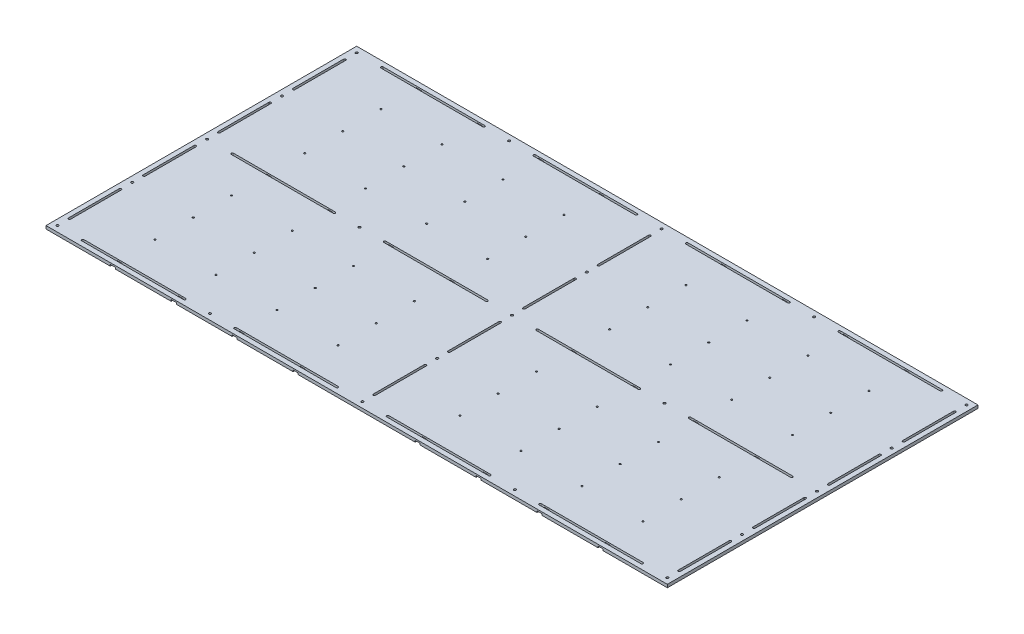
SolidWorks part; units mm, degrees
material "Pine"
ref_plane "Front" through (0, 0, 0) normal (0, 0, 1) x (1, 0, 0)
ref_plane "Top" through (0, 0, 0) normal (0, 1, 0) x (1, 0, 0)
ref_plane "Right" through (0, 0, 0) normal (1, 0, 0) x (0, 0, -1)
sketch "Sketch1" plane through (0, 0, 0) normal (0, 1, 0) x (1, 0, 0)
  line L0 (-1220, 610) -> (1220, -610) construction
  line L1 (-1220, 610) -> (1220, 610)
  line L2 (-1220, 610) -> (-1220, -610)
  line L3 (-1220, -610) -> (1220, -610)
  line L4 (1220, 610) -> (1220, -610)
  dimension "D1" = 2440
  dimension "D2" = 1220
extrude "Boss-Extrude1" add sketch "Sketch1" along normal blind 12
sketch "Sketch3" plane through (0, 0, 0) normal (0, -1, 0) x (1, 0, 0)
  line L0 (-1220, 610) -> (1220, 610) construction
  line L1 (-968, 610) -> (-948, 610)
  line L2 (-968, 610) -> (-968, -610)
  line L3 (-968, -610) -> (-948, -610)
  line L4 (-948, 610) -> (-948, -610)
  line L5 (1220, -610) -> (-1220, -610) construction
  line L7 (-1220, 610) -> (-1175, 610) construction
  line L8 (-1220, 610) -> (-1220, -610) construction
  line L9 (-1220, -610) -> (-1175, -610) construction
  line L10 (-1175, 610) -> (-1175, -610) construction
  line L11 (-22.5, 610) -> (22.5, 610) construction
  line L12 (-22.5, 610) -> (-22.5, -610) construction
  line L13 (-22.5, -610) -> (22.5, -610) construction
  line L14 (22.5, 610) -> (22.5, -610) construction
  line L15 (1220, 610) -> (1175, 610) construction
  line L16 (1220, 610) -> (1220, -610) construction
  line L17 (1220, -610) -> (1175, -610) construction
  line L18 (1175, 610) -> (1175, -610) construction
  line L19 (-1220, 610) -> (1220, 610) construction
  line L20 (-1220, 610) -> (-1220, 565) construction
  line L21 (-1220, 565) -> (1220, 565) construction
  line L22 (1220, 610) -> (1220, 565) construction
  line L23 (1220, 22.5) -> (-1220, 22.5) construction
  line L24 (1220, 22.5) -> (1220, -22.5) construction
  line L25 (1220, -22.5) -> (-1220, -22.5) construction
  line L26 (-1220, 22.5) -> (-1220, -22.5) construction
  line L27 (-1220, -610) -> (1220, -610) construction
  line L28 (-1220, -610) -> (-1220, -565) construction
  line L29 (-1220, -565) -> (1220, -565) construction
  line L30 (1220, -610) -> (1220, -565) construction
  line L31 (-1197.5, 610) -> (-1197.5, -610) construction
  line L32 (0, -610) -> (0, 610) construction
  line L33 (1197.5, -610) -> (1197.5, 610) construction
  line L34 (-958, 610) -> (-958, -610) construction
  line L35 (-728.5, 610) -> (-708.5, 610)
  line L36 (-728.5, 610) -> (-728.5, -610)
  line L37 (-728.5, -610) -> (-708.5, -610)
  line L38 (-708.5, 610) -> (-708.5, -610)
  line L39 (-718.5, 610) -> (-718.5, -610) construction
  line L40 (-489, 610) -> (-469, 610)
  line L41 (-489, 610) -> (-489, -610)
  line L42 (-489, -610) -> (-469, -610)
  line L43 (-469, 610) -> (-469, -610)
  line L44 (-479, 610) -> (-479, -610) construction
  line L45 (-249.5, 610) -> (-229.5, 610)
  line L46 (-249.5, 610) -> (-249.5, -610)
  line L47 (-249.5, -610) -> (-229.5, -610)
  line L48 (-229.5, 610) -> (-229.5, -610)
  line L49 (-239.5, 610) -> (-239.5, -610) construction
  line L50 (239.5, 610) -> (239.5, -610) construction
  line L51 (479, 610) -> (479, -610) construction
  line L52 (718.5, 610) -> (718.5, -610) construction
  line L53 (958, 610) -> (958, -610) construction
  line L54 (229.5, 610) -> (229.5, -610)
  line L55 (249.5, -610) -> (229.5, -610)
  line L56 (249.5, 610) -> (249.5, -610)
  line L57 (249.5, 610) -> (229.5, 610)
  line L58 (469, 610) -> (469, -610)
  line L59 (489, -610) -> (469, -610)
  line L60 (489, 610) -> (489, -610)
  line L61 (489, 610) -> (469, 610)
  line L62 (708.5, 610) -> (708.5, -610)
  line L63 (728.5, -610) -> (708.5, -610)
  line L64 (728.5, 610) -> (728.5, -610)
  line L65 (728.5, 610) -> (708.5, 610)
  line L66 (948, 610) -> (948, -610)
  line L67 (968, -610) -> (948, -610)
  line L68 (968, 610) -> (968, -610)
  line L69 (968, 610) -> (948, 610)
  dimension "D1" = 20
  dimension "D2" = 45
  dimension "D3" = 22.5
  dimension "D4" = 45
  dimension "D5" = 22.5
  dimension "D6" = 239.5
  dimension "D8" = 239.5
  dimension "D7" = 4
extrude "Cut-Extrude1" cut sketch "Sketch3" against normal blind 6
hole_wizard "M8 Clearance Hole1" positions "Sketch7" profile "Sketch5" hole size "M8" standard "ISO" end condition through all
sketch "Sketch7" plane through (0, 12, 0) normal (0, 1, 0) x (1, 0, 0)
  line L0 (-1197.5, -610) -> (-1197.5, 610) construction
  line L1 (0, 610) -> (0, -610) construction
  line L2 (1197.5, 610) -> (1197.5, -610) construction
  line L3 (-1197.5, 587.5) -> (-1197.5, 0) construction
  line L4 (-1197.5, 0) -> (-1197.5, -587.5) construction
  line L6 (-1220, 610) -> (-1175, 610) construction
  line L7 (-1220, -610) -> (-1175, -610) construction
  line L25 (-718.5, 0) -> (-479, 0) construction
  line L26 (-718.5, -610) -> (-718.5, 610) construction
  line L27 (-479, -610) -> (-479, 610) construction
  line L29 (479, 0) -> (718.5, 0) construction
  line L30 (479, -610) -> (479, 610) construction
  line L31 (718.5, -610) -> (718.5, 610) construction
  point P0 (-1197.5, 587.5)
  point P4 (-1197.5, 293.75)
  point P6 (-1197.5, 0)
  point P8 (-1197.5, -293.75)
  point P10 (-1197.5, -587.5)
  point P12 (0, -587.5)
  point P16 (0, 0)
  point P19 (0, 587.5)
  point P21 (1197.5, 587.5)
  point P25 (1197.5, 293.75)
  point P27 (1197.5, 0)
  point P29 (1197.5, -293.75)
  point P31 (1197.5, -587.5)
  point P33 (0, -293.75)
  point P35 (0, 293.75)
  point P109 (598.75, 0)
  point P111 (-598.75, 0)
  point P114 (-598.75, -587.5)
  point P116 (-598.75, 587.5)
  point P120 (598.75, 587.5)
  point P122 (598.75, -587.5)
  dimension "D1" = 22.5
  dimension "D2" = 22.5
sketch "Sketch5" plane through (-1197.5, 12, -587.5) normal (1, 0, 0) x (0, 0, 1)
  line L0 (0, 0) -> (0, 12)
  line L1 (0, 12) -> (4.5, 12)
  line L2 (4.5, 12) -> (4.5, 0)
  line L5 (4.5, 0) -> (0, 0)
  line L11 (0, -6.35) -> (0, 107.95) construction
  dimension "Thru Hole Dia." = 9
  dimension "Thru Hole Depth" = 12
sketch "Sketch8" plane through (0, 12, 0) normal (0, 1, 0) x (1, 0, 0)
  line L0 (-1197.5, 587.5) -> (-598.75, 587.5) construction
  line L1 (-598.75, 587.5) -> (0, 587.5) construction
  line L2 (-1197.5, 587.5) -> (-1197.5, 293.75) construction
  line L3 (-1197.5, 293.75) -> (-1197.5, 0) construction
  line L4 (-1197.5, -610) -> (-1197.5, 610) construction
  line L5 (-1197.5, 0) -> (-598.75, 0) construction
  line L6 (-598.75, 0) -> (0, 0) construction
  line L7 (-1197.5, 0) -> (-1197.5, -293.75) construction
  line L8 (-1197.5, -293.75) -> (-1197.5, -587.5) construction
  line L9 (-1197.5, -587.5) -> (-598.75, -587.5) construction
  line L10 (-598.75, -587.5) -> (0, -587.5) construction
  line L11 (-1098.125, 587.5) -> (-698.125, 587.5) construction
  line L12 (-1098.125, 591.75) -> (-698.125, 591.75)
  line L13 (-1098.125, 583.25) -> (-698.125, 583.25)
  line L14 (-99.375, 587.5) -> (-499.375, 587.5) construction
  line L15 (-99.375, 583.25) -> (-499.375, 583.25)
  line L16 (-99.375, 591.75) -> (-499.375, 591.75)
  line L17 (-1197.5, 340.625) -> (-1197.5, 540.625) construction
  line L18 (-1201.75, 340.625) -> (-1201.75, 540.625)
  line L19 (-1193.25, 340.625) -> (-1193.25, 540.625)
  line L20 (-1197.5, 46.875) -> (-1197.5, 246.875) construction
  line L21 (-1201.75, 46.875) -> (-1201.75, 246.875)
  line L22 (-1193.25, 46.875) -> (-1193.25, 246.875)
  line L23 (-1197.5, -246.875) -> (-1197.5, -46.875) construction
  line L24 (-1201.75, -246.875) -> (-1201.75, -46.875)
  line L25 (-1193.25, -246.875) -> (-1193.25, -46.875)
  line L26 (-1197.5, -540.625) -> (-1197.5, -340.625) construction
  line L27 (-1201.75, -540.625) -> (-1201.75, -340.625)
  line L28 (-1193.25, -540.625) -> (-1193.25, -340.625)
  line L29 (-1098.125, -587.5) -> (-698.125, -587.5) construction
  line L30 (-1098.125, -583.25) -> (-698.125, -583.25)
  line L31 (-1098.125, -591.75) -> (-698.125, -591.75)
  line L32 (-99.375, -587.5) -> (-499.375, -587.5) construction
  line L33 (-99.375, -591.75) -> (-499.375, -591.75)
  line L34 (-99.375, -583.25) -> (-499.375, -583.25)
  line L35 (-99.375, 0) -> (-499.375, 0) construction
  line L36 (-99.375, -4.25) -> (-499.375, -4.25)
  line L37 (-99.375, 4.25) -> (-499.375, 4.25)
  line L38 (-1098.125, 0) -> (-698.125, 0) construction
  line L39 (-1098.125, 4.25) -> (-698.125, 4.25)
  line L40 (-1098.125, -4.25) -> (-698.125, -4.25)
  line L41 (0, -50) -> (0, 50) construction
  line L42 (1098.125, 587.5) -> (698.125, 587.5) construction
  line L43 (1098.125, 591.75) -> (698.125, 591.75)
  line L44 (1098.125, 583.25) -> (698.125, 583.25)
  line L45 (99.375, 587.5) -> (499.375, 587.5) construction
  line L46 (99.375, 583.25) -> (499.375, 583.25)
  line L47 (99.375, 591.75) -> (499.375, 591.75)
  line L48 (1197.5, 340.625) -> (1197.5, 540.625) construction
  line L49 (1201.75, 340.625) -> (1201.75, 540.625)
  line L50 (1193.25, 340.625) -> (1193.25, 540.625)
  line L51 (1197.5, 46.875) -> (1197.5, 246.875) construction
  line L52 (1201.75, 46.875) -> (1201.75, 246.875)
  line L53 (1193.25, 46.875) -> (1193.25, 246.875)
  line L54 (1197.5, -246.875) -> (1197.5, -46.875) construction
  line L55 (1201.75, -246.875) -> (1201.75, -46.875)
  line L56 (1193.25, -246.875) -> (1193.25, -46.875)
  line L57 (1197.5, -540.625) -> (1197.5, -340.625) construction
  line L58 (1201.75, -540.625) -> (1201.75, -340.625)
  line L59 (1193.25, -540.625) -> (1193.25, -340.625)
  line L60 (1098.125, -587.5) -> (698.125, -587.5) construction
  line L61 (1098.125, -583.25) -> (698.125, -583.25)
  line L62 (1098.125, -591.75) -> (698.125, -591.75)
  line L63 (99.375, -587.5) -> (499.375, -587.5) construction
  line L64 (99.375, -591.75) -> (499.375, -591.75)
  line L65 (99.375, -583.25) -> (499.375, -583.25)
  line L66 (99.375, 0) -> (499.375, 0) construction
  line L67 (99.375, -4.25) -> (499.375, -4.25)
  line L68 (99.375, 4.25) -> (499.375, 4.25)
  line L69 (1098.125, 0) -> (698.125, 0) construction
  line L70 (1098.125, 4.25) -> (698.125, 4.25)
  line L71 (1098.125, -4.25) -> (698.125, -4.25)
  line L72 (598.75, -587.5) -> (0, -587.5) construction
  line L73 (1197.5, -587.5) -> (598.75, -587.5) construction
  line L74 (1197.5, -293.75) -> (1197.5, -587.5) construction
  line L75 (1197.5, 0) -> (1197.5, -293.75) construction
  line L76 (598.75, 0) -> (0, 0) construction
  line L77 (1197.5, 0) -> (598.75, 0) construction
  line L78 (1197.5, 293.75) -> (1197.5, 0) construction
  line L79 (1197.5, 587.5) -> (1197.5, 293.75) construction
  line L80 (598.75, 587.5) -> (0, 587.5) construction
  line L81 (1197.5, 587.5) -> (598.75, 587.5) construction
  line L83 (0, 587.5) -> (0, 293.75) construction
  line L84 (0, 293.75) -> (0, 0) construction
  line L85 (0, 0) -> (0, -293.75) construction
  line L86 (0, -293.75) -> (0, -587.5) construction
  line L87 (0, 340.625) -> (0, 540.625) construction
  line L88 (-4.25, 340.625) -> (-4.25, 540.625)
  line L89 (4.25, 340.625) -> (4.25, 540.625)
  line L90 (0, 46.875) -> (0, 246.875) construction
  line L91 (-4.25, 46.875) -> (-4.25, 246.875)
  line L92 (4.25, 46.875) -> (4.25, 246.875)
  line L93 (0, -246.875) -> (0, -46.875) construction
  line L94 (-4.25, -246.875) -> (-4.25, -46.875)
  line L95 (4.25, -246.875) -> (4.25, -46.875)
  line L96 (0, -540.625) -> (0, -340.625) construction
  line L97 (-4.25, -540.625) -> (-4.25, -340.625)
  line L98 (4.25, -540.625) -> (4.25, -340.625)
  arc A0 (-1098.125, 591.75) -> (-1098.125, 583.25) centre (-1098.125, 587.5) ccw
  arc A1 (-698.125, 583.25) -> (-698.125, 591.75) centre (-698.125, 587.5) ccw
  arc A2 (-99.375, 583.25) -> (-99.375, 591.75) centre (-99.375, 587.5) ccw
  arc A3 (-499.375, 591.75) -> (-499.375, 583.25) centre (-499.375, 587.5) ccw
  arc A4 (-1201.75, 340.625) -> (-1193.25, 340.625) centre (-1197.5, 340.625) ccw
  arc A5 (-1193.25, 540.625) -> (-1201.75, 540.625) centre (-1197.5, 540.625) ccw
  arc A6 (-1201.75, 46.875) -> (-1193.25, 46.875) centre (-1197.5, 46.875) ccw
  arc A7 (-1193.25, 246.875) -> (-1201.75, 246.875) centre (-1197.5, 246.875) ccw
  arc A8 (-1201.75, -246.875) -> (-1193.25, -246.875) centre (-1197.5, -246.875) ccw
  arc A9 (-1193.25, -46.875) -> (-1201.75, -46.875) centre (-1197.5, -46.875) ccw
  arc A10 (-1201.75, -540.625) -> (-1193.25, -540.625) centre (-1197.5, -540.625) ccw
  arc A11 (-1193.25, -340.625) -> (-1201.75, -340.625) centre (-1197.5, -340.625) ccw
  arc A12 (-1098.125, -583.25) -> (-1098.125, -591.75) centre (-1098.125, -587.5) ccw
  arc A13 (-698.125, -591.75) -> (-698.125, -583.25) centre (-698.125, -587.5) ccw
  arc A14 (-99.375, -591.75) -> (-99.375, -583.25) centre (-99.375, -587.5) ccw
  arc A15 (-499.375, -583.25) -> (-499.375, -591.75) centre (-499.375, -587.5) ccw
  arc A16 (-99.375, -4.25) -> (-99.375, 4.25) centre (-99.375, 0) ccw
  arc A17 (-499.375, 4.25) -> (-499.375, -4.25) centre (-499.375, 0) ccw
  arc A18 (-1098.125, 4.25) -> (-1098.125, -4.25) centre (-1098.125, 0) ccw
  arc A19 (-698.125, -4.25) -> (-698.125, 4.25) centre (-698.125, 0) ccw
  arc A20 (1098.125, 591.75) -> (1098.125, 583.25) centre (1098.125, 587.5) cw
  arc A21 (698.125, 583.25) -> (698.125, 591.75) centre (698.125, 587.5) cw
  arc A22 (99.375, 583.25) -> (99.375, 591.75) centre (99.375, 587.5) cw
  arc A23 (499.375, 591.75) -> (499.375, 583.25) centre (499.375, 587.5) cw
  arc A24 (1201.75, 340.625) -> (1193.25, 340.625) centre (1197.5, 340.625) cw
  arc A25 (1193.25, 540.625) -> (1201.75, 540.625) centre (1197.5, 540.625) cw
  arc A26 (1201.75, 46.875) -> (1193.25, 46.875) centre (1197.5, 46.875) cw
  arc A27 (1193.25, 246.875) -> (1201.75, 246.875) centre (1197.5, 246.875) cw
  arc A28 (1201.75, -246.875) -> (1193.25, -246.875) centre (1197.5, -246.875) cw
  arc A29 (1193.25, -46.875) -> (1201.75, -46.875) centre (1197.5, -46.875) cw
  arc A30 (1201.75, -540.625) -> (1193.25, -540.625) centre (1197.5, -540.625) cw
  arc A31 (1193.25, -340.625) -> (1201.75, -340.625) centre (1197.5, -340.625) cw
  arc A32 (1098.125, -583.25) -> (1098.125, -591.75) centre (1098.125, -587.5) cw
  arc A33 (698.125, -591.75) -> (698.125, -583.25) centre (698.125, -587.5) cw
  arc A34 (99.375, -591.75) -> (99.375, -583.25) centre (99.375, -587.5) cw
  arc A35 (499.375, -583.25) -> (499.375, -591.75) centre (499.375, -587.5) cw
  arc A36 (99.375, -4.25) -> (99.375, 4.25) centre (99.375, 0) cw
  arc A37 (499.375, 4.25) -> (499.375, -4.25) centre (499.375, 0) cw
  arc A38 (1098.125, 4.25) -> (1098.125, -4.25) centre (1098.125, 0) cw
  arc A39 (698.125, -4.25) -> (698.125, 4.25) centre (698.125, 0) cw
  arc A40 (-4.25, 340.625) -> (4.25, 340.625) centre (0, 340.625) ccw
  arc A41 (4.25, 540.625) -> (-4.25, 540.625) centre (0, 540.625) ccw
  arc A42 (-4.25, 46.875) -> (4.25, 46.875) centre (0, 46.875) ccw
  arc A43 (4.25, 246.875) -> (-4.25, 246.875) centre (0, 246.875) ccw
  arc A44 (-4.25, -246.875) -> (4.25, -246.875) centre (0, -246.875) ccw
  arc A45 (4.25, -46.875) -> (-4.25, -46.875) centre (0, -46.875) ccw
  arc A46 (-4.25, -540.625) -> (4.25, -540.625) centre (0, -540.625) ccw
  arc A47 (4.25, -340.625) -> (-4.25, -340.625) centre (0, -340.625) ccw
  point P25 (-898.125, 587.5)
  point P31 (-299.375, 587.5)
  point P38 (-1197.5, 440.625)
  point P45 (-1197.5, 146.875)
  point P52 (-1197.5, -146.875)
  point P59 (-1197.5, -440.625)
  point P66 (-898.125, -587.5)
  point P73 (-299.375, -587.5)
  point P80 (-299.375, 0)
  point P87 (-898.125, 0)
  point P98 (898.125, 587.5)
  point P105 (299.375, 587.5)
  point P112 (1197.5, 440.625)
  point P119 (1197.5, 146.875)
  point P126 (1197.5, -146.875)
  point P133 (1197.5, -440.625)
  point P140 (898.125, -587.5)
  point P147 (299.375, -587.5)
  point P154 (299.375, 0)
  point P161 (898.125, 0)
  point P183 (0, 440.625)
  point P190 (0, 146.875)
  point P197 (0, -146.875)
  point P204 (0, -440.625)
  dimension "D1" = 8.5
  dimension "D2" = 400
  dimension "D3" = 200
  dimension "D4" = 8.5
  dimension "D5" = 2
extrude "Cut-Extrude2" cut sketch "Sketch8" against normal through all
hole_wizard "Ø6.5 (6.5) Diameter Hole1" positions "Sketch9" profile "Sketch10" hole size "Ø6.5" standard "ISO"
sketch "Sketch9" plane through (0, 12, 0) normal (0, 1, 0) x (1, 0, 0)
  line L0 (-958, -610) -> (-958, 610) construction
  line L3 (-958, 443.75) -> (-958, 293.75) construction
  line L4 (-958, 293.75) -> (-958, 143.75) construction
  line L7 (-1220, 610) -> (1220, 610) construction
  line L9 (-958, -143.75) -> (-958, -293.75) construction
  line L10 (-958, -293.75) -> (-958, -443.75) construction
  line L12 (-1220, -610) -> (1220, -610) construction
  line L13 (-718.5, 443.75) -> (-718.5, 293.75) construction
  line L14 (-718.5, 293.75) -> (-718.5, 143.75) construction
  line L17 (-718.5, -143.75) -> (-718.5, -293.75) construction
  line L18 (-718.5, -293.75) -> (-718.5, -443.75) construction
  line L19 (-479, 443.75) -> (-479, 293.75) construction
  line L20 (-479, 293.75) -> (-479, 143.75) construction
  line L23 (-479, -143.75) -> (-479, -293.75) construction
  line L24 (-479, -293.75) -> (-479, -443.75) construction
  line L25 (-239.5, 443.75) -> (-239.5, 293.75) construction
  line L26 (-239.5, 293.75) -> (-239.5, 143.75) construction
  line L29 (-239.5, -143.75) -> (-239.5, -293.75) construction
  line L30 (-239.5, -293.75) -> (-239.5, -443.75) construction
  line L31 (0, 443.75) -> (0, 293.75) construction
  line L32 (0, 293.75) -> (0, 143.75) construction
  line L35 (0, -143.75) -> (0, -293.75) construction
  line L36 (0, -293.75) -> (0, -443.75) construction
  line L37 (239.5, 443.75) -> (239.5, 293.75) construction
  line L38 (239.5, 293.75) -> (239.5, 143.75) construction
  line L41 (239.5, -143.75) -> (239.5, -293.75) construction
  line L42 (239.5, -293.75) -> (239.5, -443.75) construction
  line L43 (479, 443.75) -> (479, 293.75) construction
  line L44 (479, 293.75) -> (479, 143.75) construction
  line L47 (479, -143.75) -> (479, -293.75) construction
  line L48 (479, -293.75) -> (479, -443.75) construction
  line L49 (718.5, 443.75) -> (718.5, 293.75) construction
  line L50 (718.5, 293.75) -> (718.5, 143.75) construction
  line L53 (718.5, -143.75) -> (718.5, -293.75) construction
  line L54 (718.5, -293.75) -> (718.5, -443.75) construction
  line L55 (958, 443.75) -> (958, 293.75) construction
  line L56 (958, 293.75) -> (958, 143.75) construction
  line L59 (958, -143.75) -> (958, -293.75) construction
  line L60 (958, -293.75) -> (958, -443.75) construction
  point P0 (-958, 443.75)
  point P4 (-958, 293.75)
  point P6 (-958, 143.75)
  point P14 (-958, -143.75)
  point P16 (-958, -293.75)
  point P18 (-958, -443.75)
  point P54 (-718.5, 443.75)
  point P55 (-718.5, 293.75)
  point P56 (-718.5, 143.75)
  point P59 (-718.5, -143.75)
  point P60 (-718.5, -293.75)
  point P61 (-718.5, -443.75)
  point P70 (-479, 443.75)
  point P71 (-479, 293.75)
  point P72 (-479, 143.75)
  point P75 (-479, -143.75)
  point P76 (-479, -293.75)
  point P77 (-479, -443.75)
  point P86 (-239.5, 443.75)
  point P87 (-239.5, 293.75)
  point P88 (-239.5, 143.75)
  point P91 (-239.5, -143.75)
  point P92 (-239.5, -293.75)
  point P93 (-239.5, -443.75)
  point P102 (0, 443.75) [skipped]
  point P103 (0, 293.75) [skipped]
  point P104 (0, 143.75) [skipped]
  point P105 (0, 23.75) [skipped]
  point P106 (0, -70) [skipped]
  point P107 (0, -143.75) [skipped]
  point P108 (0, -293.75) [skipped]
  point P109 (0, -443.75) [skipped]
  point P118 (239.5, 443.75)
  point P119 (239.5, 293.75)
  point P120 (239.5, 143.75)
  point P123 (239.5, -143.75)
  point P124 (239.5, -293.75)
  point P125 (239.5, -443.75)
  point P134 (479, 443.75)
  point P135 (479, 293.75)
  point P136 (479, 143.75)
  point P139 (479, -143.75)
  point P140 (479, -293.75)
  point P141 (479, -443.75)
  point P150 (718.5, 443.75)
  point P151 (718.5, 293.75)
  point P152 (718.5, 143.75)
  point P155 (718.5, -143.75)
  point P156 (718.5, -293.75)
  point P157 (718.5, -443.75)
  point P166 (958, 443.75)
  point P167 (958, 293.75)
  point P168 (958, 143.75)
  point P171 (958, -143.75)
  point P172 (958, -293.75)
  point P173 (958, -443.75)
  point P183 (958, -70) [skipped]
  point P184 (718.5, -70) [skipped]
  point P185 (479, -70) [skipped]
  point P186 (239.5, -70) [skipped]
  point P187 (-239.5, -70) [skipped]
  point P188 (-479, -70) [skipped]
  point P189 (-718.5, -70) [skipped]
  dimension "D1" = 150
  dimension "D2" = 166.25
  dimension "D3" = 166.25
  dimension "D4" = 9
  dimension "D5" = 239.5
sketch "Sketch10" plane through (-958, 12, -443.75) normal (1, 0, 0) x (0, 0, 1)
  line L0 (0, 0) -> (0, 12)
  line L1 (0, 12) -> (3.25, 12)
  line L2 (3.25, 12) -> (3.25, 0)
  line L5 (3.25, 0) -> (0, 0)
  line L11 (0, -6.35) -> (0, 107.95) construction
  dimension "Thru Hole Dia." = 6.5
  dimension "Thru Hole Depth" = 12
hole_wizard "Ø9.0 (9) Diameter Hole1" positions "Sketch11" profile "Sketch12" hole size "Ø9.0" standard "ISO" end condition through all
sketch "Sketch11" plane through (0, 12, 0) normal (0, 1, 0) x (1, 0, 0)
  point P0 (-1197.5, 293.75)
  point P3 (-1197.5, -293.75)
  point P6 (-598.75, -587.5)
  point P9 (598.75, -587.5)
  point P12 (1197.5, -293.75)
  point P15 (1197.5, 293.75)
  point P18 (598.75, 587.5)
  point P21 (-598.75, 587.5)
  point P24 (0, 293.75)
  point P27 (0, -293.75)
sketch "Sketch12" plane through (-1197.5, 12, -293.75) normal (1, 0, 0) x (0, 0, 1)
  line L0 (0, 0) -> (0, 12)
  line L1 (0, 12) -> (4.5, 12)
  line L2 (4.5, 12) -> (4.5, 0)
  line L5 (4.5, 0) -> (0, 0)
  line L11 (0, -6.35) -> (0, 107.95) construction
  dimension "Thru Hole Dia." = 9
  dimension "Thru Hole Depth" = 12
hole_wizard "CBORE for M8 Hex Socket Head Cap Screw1" positions "Sketch13" profile "Sketch14" counterbore size "M8" standard "ISO"
sketch "Sketch13" plane through (0, 9, 0) normal (0, 1, 0) x (1, 0, 0)
  point P0 (-1197.5, 587.5)
  point P3 (-1197.5, 293.75)
  point P6 (-1197.5, 0)
  point P9 (-1197.5, -293.75)
  point P12 (-1197.5, -587.5)
  point P15 (-598.75, -587.5)
  point P18 (0, -587.5)
  point P21 (0, -293.75)
  point P24 (0, 0)
  point P27 (0, 293.75)
  point P30 (0, 587.5)
  point P33 (598.75, 587.5)
  point P36 (1197.5, 587.5)
  point P39 (1197.5, 293.75)
  point P42 (1197.5, 0)
  point P45 (1197.5, -293.75)
  point P48 (1197.5, -587.5)
  point P51 (598.75, -587.5)
  point P54 (598.75, 0)
  point P57 (-598.75, 0)
sketch "Sketch14" plane through (-1197.5, 9, -587.5) normal (1, 0, 0) x (0, 0, 1)
  line L0 (0, 0) -> (0, 9)
  line L1 (0, 9) -> (4.5, 9)
  line L3 (4.5, 9) -> (4.5, 6)
  line L4 (4.5, 6) -> (7.5, 6)
  line L5 (7.5, 6) -> (7.5, 0)
  line L7 (7.5, 0) -> (0, 0)
  line L11 (0, -6.35) -> (0, 107.95) construction
  dimension "Thru Hole Dia." = 9
  dimension "Thru Hole Depth" = 9
  dimension "C'Bore Dia." = 15
  dimension "C'Bore Depth" = 6
sketch "Sketch15" plane through (0, 12, 0) normal (0, 1, 0) x (1, 0, 0)
  line L1 (-949.3397, 443.75) -> (-953.6699, 451.25)
  line L2 (-953.6699, 451.25) -> (-962.3301, 451.25)
  line L3 (-962.3301, 451.25) -> (-966.6603, 443.75)
  line L4 (-966.6603, 443.75) -> (-962.3301, 436.25)
  line L5 (-962.3301, 436.25) -> (-953.6699, 436.25)
  line L6 (-953.6699, 436.25) -> (-949.3397, 443.75)
  circle A0 centre (-958, 443.75) radius 7.5 construction
  dimension "D1" = 15
